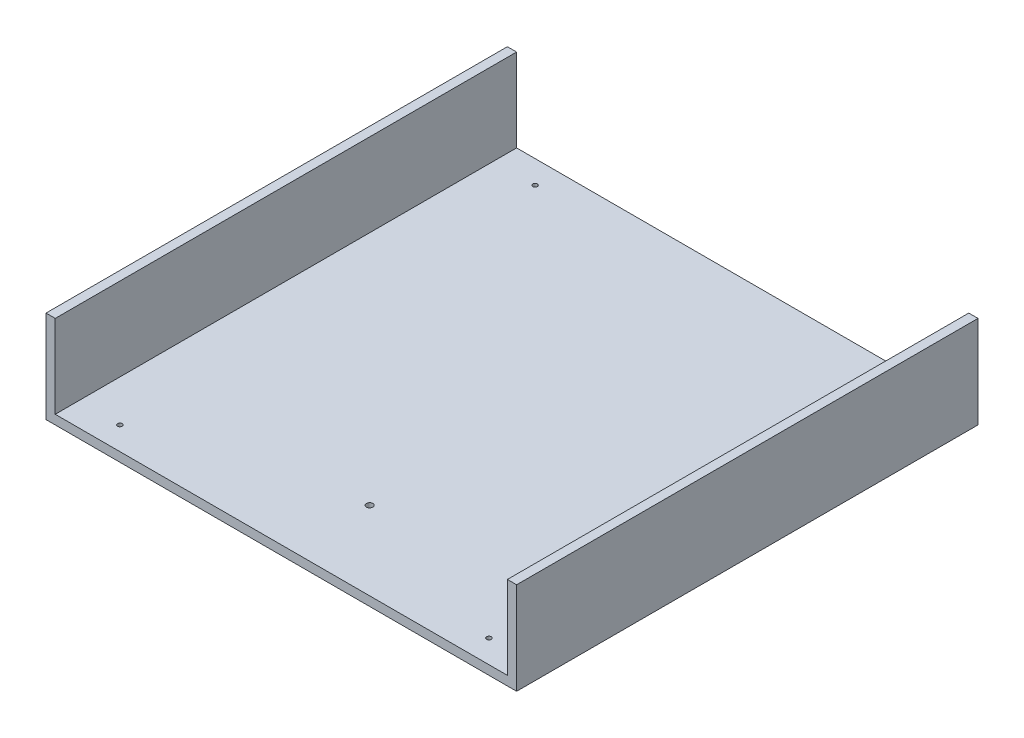
SolidWorks part; units mm, degrees
ref_plane "Alzado" through (0, 0, 0) normal (0, 0, 1) x (1, 0, 0)
ref_plane "Planta" through (0, 0, 0) normal (0, 1, 0) x (1, 0, 0)
ref_plane "Vista lateral" through (0, 0, 0) normal (1, 0, 0) x (0, 0, -1)
sketch "Croquis2" plane through (0, 0, 0) normal (0, 1, 0) x (1, 0, 0)
  line L1 (-25.5, -25) -> (25.5, -25)
  line L2 (-25.5, -25) -> (-25.5, 25)
  line L3 (-25.5, 25) -> (25.5, 25)
  line L4 (25.5, -25) -> (25.5, 25)
  line L5 (0, 25) -> (0, -25) construction
  line L6 (-25.5, 0) -> (25.5, 0) construction
  point P0 (0, 0)
  dimension "D1" = 50
  dimension "D2" = 51
extrude "Saliente-Extruir3" add sketch "Croquis2" along normal blind 10
sketch "Croquis6" plane through (0, 0, 25) normal (0, 0, 1) x (1, 0, 0)
  line L0 (-25.5, 0) -> (25.5, 0) construction
  line L1 (-24.5, 1) -> (24.5, 1)
  line L2 (-24.5, 1) -> (-24.5, 10)
  line L3 (-24.5, 10) -> (24.5, 10)
  line L4 (24.5, 1) -> (24.5, 10)
  line L5 (-25.5, 10) -> (-25.5, 0) construction
  line L6 (25.5, 10) -> (25.5, 0) construction
  dimension "D1" = 1
  dimension "D2" = 1
  dimension "D3" = 1
  dimension "D4" = 9
extrude "Cortar-Extruir4" cut sketch "Croquis6" against normal blind 50
sketch "Croquis7" plane through (0, 1, 0) normal (0, 1, 0) x (1, 0, 0)
  line L0 (-24.5, 25) -> (-24.5, -25) construction
  line L1 (-24.5, 25) -> (24.5, 25) construction
  circle A0 centre (-20, 22.5) radius 0.25
  dimension "D1" = 0.5
  dimension "D2" = 4.5
  dimension "D3" = 2.5
extrude "Cortar-Extruir5" cut sketch "Croquis7" against normal up to next
sketch "Croquis8" plane through (0, 1, 0) normal (0, 1, 0) x (1, 0, 0)
sketch "Croquis10" plane through (0, 1, 0) normal (0, 1, 0) x (1, 0, 0)
  line L0 (24.5, 25) -> (24.5, -25) construction
  line L1 (-24.5, 25) -> (24.5, 25) construction
  circle A0 centre (20, 22.5) radius 0.25
  dimension "D1" = 0.5
  dimension "D2" = 4.5
  dimension "D3" = 2.5
extrude "Cortar-Extruir7" cut sketch "Croquis10" against normal up to next
sketch "Croquis11" plane through (0, 1, 0) normal (0, 1, 0) x (1, 0, 0)
  line L0 (-24.5, -25) -> (24.5, -25) construction
  line L1 (-24.5, 25) -> (-24.5, -25) construction
  circle A0 centre (-20, -22.5) radius 0.25
  dimension "D1" = 0.5
  dimension "D2" = 2.5
  dimension "D3" = 4.5
extrude "Cortar-Extruir8" cut sketch "Croquis11" against normal up to next
sketch "Croquis12" plane through (0, 1, 0) normal (0, 1, 0) x (1, 0, 0)
  line L0 (-24.5, -25) -> (24.5, -25) construction
  line L1 (24.5, 25) -> (24.5, -25) construction
  circle A0 centre (20, -22.5) radius 0.25
  dimension "D1" = 0.5
  dimension "D2" = 2.5
  dimension "D3" = 4.5
extrude "Cortar-Extruir9" cut sketch "Croquis12" against normal up to next
sketch "Croquis13" plane through (0, 1, 0) normal (0, 1, 0) x (1, 0, 0)
  line L8 (-24.5, -25) -> (24.5, -25) construction
  line L9 (-24.5, 25) -> (-24.5, -25) construction
  circle A1 centre (1.0774, -16.5) radius 0.35
  dimension "D3" = 0.7
  dimension "D1" = 8.5
  dimension "D2" = 25.5774
extrude "Cortar-Extruir10" cut sketch "Croquis13" against normal up to next
